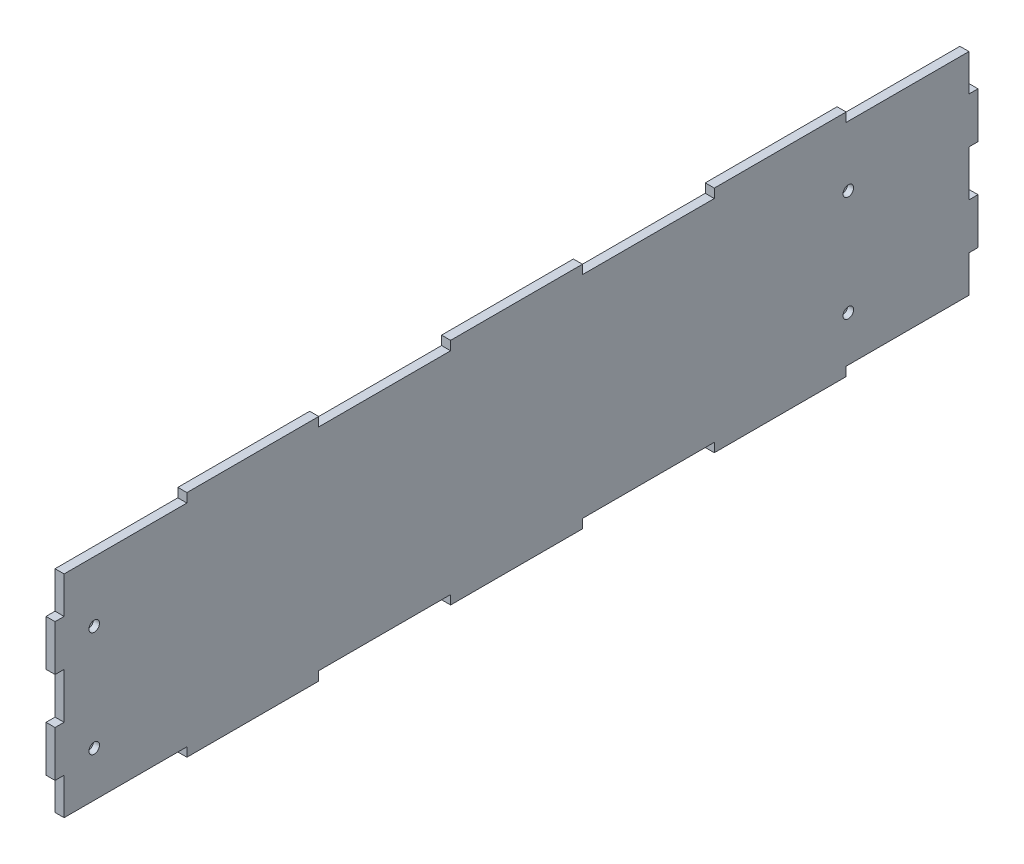
SolidWorks part; units mm, degrees
material "Pin"
ref_plane "Plan de face" through (0, 0, 0) normal (0, 0, 1) x (1, 0, 0)
ref_plane "Plan de dessus" through (0, 0, 0) normal (0, 1, 0) x (1, 0, 0)
ref_plane "Plan de droite" through (0, 0, 0) normal (1, 0, 0) x (0, 0, -1)
sketch "Esquisse3" plane through (0, 0, 0) normal (1, 0, 0) x (0, 0, -1)
  line L0 (109.2857, 38) -> (65.5714, 38)
  line L1 (150, 35) -> (109.2857, 35)
  line L3 (150, -35) -> (109.2857, -35)
  line L6 (109.2857, -38) -> (65.5714, -38)
  line L8 (109.2857, 38) -> (109.2857, 35)
  line L9 (65.5714, -38) -> (65.5714, -35)
  line L10 (21.8571, 38) -> (21.8571, 35)
  line L11 (-21.8571, -38) -> (-21.8571, -35)
  line L12 (-65.5714, 38) -> (-65.5714, 35)
  line L13 (-109.2857, -38) -> (-109.2857, -35)
  line L14 (109.2857, -35) -> (109.2857, -38)
  line L15 (65.5714, 35) -> (65.5714, 38)
  line L16 (21.8571, -35) -> (21.8571, -38)
  line L17 (-21.8571, 35) -> (-21.8571, 38)
  line L18 (-65.5714, -35) -> (-65.5714, -38)
  line L19 (-109.2857, 35) -> (-109.2857, 38)
  line L20 (-109.2857, -35) -> (-150, -35)
  line L21 (153, -38) -> (-153, -38) construction
  line L22 (-65.5714, -38) -> (-109.2857, -38)
  line L23 (150, -35) -> (-150, -35) construction
  line L24 (-21.8571, -35) -> (-65.5714, -35)
  line L25 (21.8571, -38) -> (-21.8571, -38)
  line L26 (65.5714, -35) -> (21.8571, -35)
  line L27 (153, -38) -> (109.2857, -38) construction
  line L28 (-109.2857, -38) -> (-153, -38) construction
  line L29 (65.5714, 35) -> (21.8571, 35)
  line L30 (153, 38) -> (-153, 38) construction
  line L31 (21.8571, 38) -> (-21.8571, 38)
  line L32 (150, 35) -> (-150, 35) construction
  line L33 (-21.8571, 35) -> (-65.5714, 35)
  line L34 (-65.5714, 38) -> (-109.2857, 38)
  line L35 (-109.2857, 35) -> (-150, 35)
  line L36 (109.2857, 38) -> (153, 38) construction
  line L37 (-109.2857, 38) -> (-153, 38) construction
  line L38 (153, -38) -> (-153, 38) construction
  line L43 (153, 38) -> (153, -38) construction
  line L45 (150, 35) -> (150, -35) construction
  line L49 (-153, 38) -> (-153, -38) construction
  line L51 (-150, 35) -> (-150, -35) construction
  line L53 (153, 22.8) -> (153, 7.6)
  line L59 (-153, -22.8) -> (-153, -7.6)
  line L65 (150, 35) -> (150, 22.8)
  line L66 (153, 22.8) -> (150, 22.8)
  line L67 (-153, 7.6) -> (-150, 7.6)
  line L68 (153, -7.6) -> (150, -7.6)
  line L69 (-153, -22.8) -> (-150, -22.8)
  line L70 (-150, 35) -> (-150, 22.8)
  line L71 (-150, 22.8) -> (-153, 22.8)
  line L72 (150, 7.6) -> (153, 7.6)
  line L73 (-150, -7.6) -> (-153, -7.6)
  line L74 (150, -22.8) -> (153, -22.8)
  line L75 (153, 38) -> (153, 22.8) construction
  line L76 (153, -22.8) -> (153, -38) construction
  line L77 (-153, 7.6) -> (-153, 22.8)
  line L78 (-150, 7.6) -> (-150, -7.6)
  line L79 (-150, -22.8) -> (-150, -35)
  line L80 (150, 7.6) -> (150, -7.6)
  line L81 (150, -22.8) -> (150, -35)
  line L82 (153, -7.6) -> (153, -22.8)
  point P48 (-153, 15.2)
  dimension "D1" = 300
  dimension "D2" = 70
  dimension "D4" = 306
  dimension "D3" = 3
extrude "Boss.-Extru.3" add sketch "Esquisse3" along normal blind 3
hole_wizard "Diamètre du perçage Ø3.5 (3.5)1" positions "Esquisse4" profile "Esquisse5" hole size "Ø3.5" standard "Ansi Metric"
sketch "Esquisse4" plane through (3, 0, 0) normal (1, 0, 0) x (0, 0, -1)
  point P0 (110, 15)
  point P3 (110, -20)
  point P6 (-140, 15)
  point P9 (-140, -20)
sketch "Esquisse5" plane through (3, 15, -110) normal (0, 1, 0) x (0, 0, -1)
  line L0 (0, 0) -> (0, 3.0515)
  line L1 (0, 3.0515) -> (1.75, 2)
  line L2 (1.75, 2) -> (1.75, 0)
  line L5 (1.75, 0) -> (0, 0)
  line L10 (0, 3.0515) -> (-1.75, 2) construction
  line L11 (0, -6.35) -> (0, 107.95) construction
  dimension "Diamètre du perçage" = 3.5
  dimension "Profondeur du perçage" = 2
  dimension "Angle de pointe" = 118
